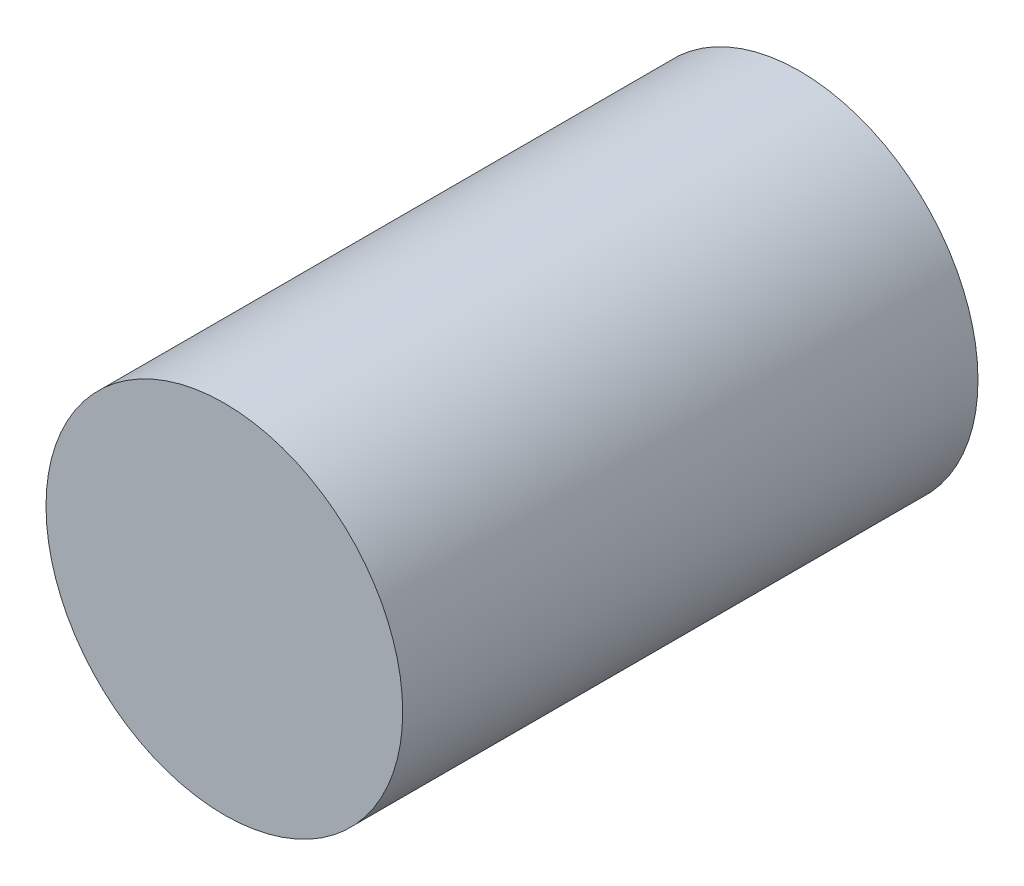
SolidWorks part; units mm, degrees
ref_plane "Front Plane" through (0, 0, 0) normal (0, 0, 1) x (1, 0, 0)
ref_plane "Top Plane" through (0, 0, 0) normal (0, 1, 0) x (1, 0, 0)
ref_plane "Right Plane" through (0, 0, 0) normal (1, 0, 0) x (0, 0, -1)
sketch "Sketch1" plane through (0, 0, 0) normal (0, 0, 1) x (1, 0, 0)
  circle A0 centre (0, 0) radius 15.5
extrude "Boss-Extrude1" add sketch "Sketch1" along normal blind 50
